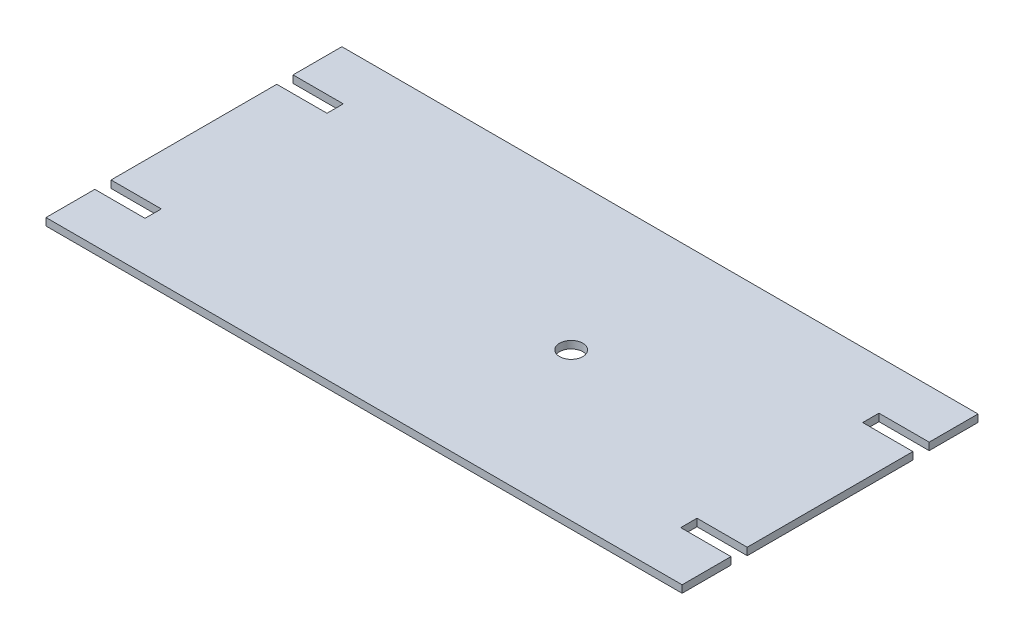
SolidWorks part; units mm, degrees
ref_plane "Front Plane" through (0, 0, 0) normal (0, 0, 1) x (1, 0, 0)
ref_plane "Top Plane" through (0, 0, 0) normal (0, 1, 0) x (1, 0, 0)
ref_plane "Right Plane" through (0, 0, 0) normal (1, 0, 0) x (0, 0, -1)
sketch "Sketch1" plane through (0, 0, 0) normal (0, 1, 0) x (1, 0, 0)
  line L0 (-215, 0) -> (215, 0) construction
  line L1 (-215, -100) -> (215, -100)
  line L2 (-215, -100) -> (-215, 100)
  line L3 (-215, 100) -> (215, 100)
  line L4 (215, -100) -> (215, 100)
  line L5 (-215, -100) -> (215, 100) construction
  line L6 (-215, 100) -> (215, -100) construction
  line L10 (0, 100) -> (0, -100) construction
  line L12 (-231.0538, -56.0021) -> (-181.0538, -56.0021)
  line L13 (-181.0538, -56.0021) -> (-181.0538, -67.0021)
  line L14 (-181.0538, -67.0021) -> (-231.0538, -67.0021)
  line L15 (-231.0538, -67.0021) -> (-231.0538, -56.0021)
  line L16 (-231.0538, 67.0021) -> (-231.0538, 56.0021)
  line L17 (-181.0538, 67.0021) -> (-231.0538, 67.0021)
  line L18 (-181.0538, 56.0021) -> (-181.0538, 67.0021)
  line L19 (-231.0538, 56.0021) -> (-181.0538, 56.0021)
  line L20 (231.0538, -67.0021) -> (231.0538, -56.0021)
  line L21 (181.0538, -67.0021) -> (231.0538, -67.0021)
  line L22 (181.0538, -56.0021) -> (181.0538, -67.0021)
  line L23 (231.0538, -56.0021) -> (181.0538, -56.0021)
  line L24 (181.0538, 67.0021) -> (231.0538, 67.0021)
  line L25 (181.0538, 56.0021) -> (181.0538, 67.0021)
  line L26 (231.0538, 56.0021) -> (181.0538, 56.0021)
  line L27 (231.0538, 67.0021) -> (231.0538, 56.0021)
  point P0 (0, 0)
  dimension "D1" = 430
  dimension "D2" = 200
  dimension "D3" = 50
  dimension "D5" = 11
extrude "Boss-Extrude1" add sketch "Sketch1" along normal blind 5
sketch "Sketch2" plane through (0, 5, 0) normal (0, 1, 0) x (1, 0, 0)
  line L1 (-215, 100) -> (215, 100) construction
  line L2 (-215, -56.0021) -> (-215, 56.0021) construction
  circle A0 centre (40, 0) radius 7.85
  dimension "D3" = 15.7
  dimension "D1" = 255
  dimension "D2" = 100
extrude "Cut-Extrude1" cut sketch "Sketch2" against normal through all
